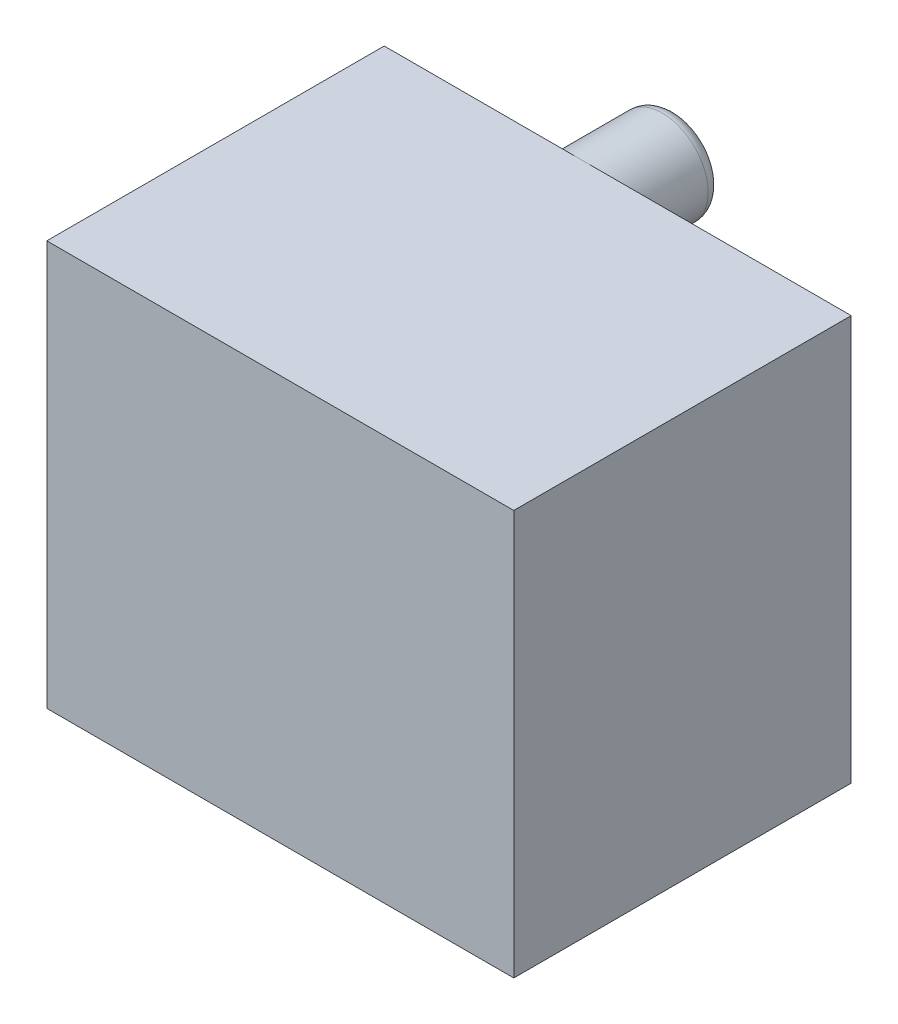
SolidWorks part; units mm, degrees
ref_plane "Front Plane" through (0, 0, 0) normal (0, 0, 1) x (1, 0, 0)
ref_plane "Top Plane" through (0, 0, 0) normal (0, 1, 0) x (1, 0, 0)
ref_plane "Right Plane" through (0, 0, 0) normal (1, 0, 0) x (0, 0, -1)
sketch "Sketch1" plane through (0, 0, 0) normal (0, 0, 1) x (1, 0, 0)
  line L1 (-8.65, 7.5) -> (8.65, 7.5)
  line L2 (-8.65, 7.5) -> (-8.65, -7.5)
  line L3 (-8.65, -7.5) -> (8.65, -7.5)
  line L4 (8.65, 7.5) -> (8.65, -7.5)
  line L5 (-8.65, 7.5) -> (8.65, -7.5) construction
  line L6 (-8.65, -7.5) -> (8.65, 7.5) construction
  point P0 (0, 0)
  dimension "D1" = 17.3
  dimension "D2" = 15
extrude "Boss-Extrude1" add sketch "Sketch1" along normal blind 12.5
sketch "Sketch2" plane through (-8.65, 0, 0) normal (-1, 0, 0) x (0, 0, 1)
  line L0 (12.5, 0) -> (0, 0) construction
  line L1 (12.5, 7.5) -> (12.5, -7.5) construction
  line L2 (0, 7.5) -> (0, -7.5) construction
  line L3 (10.5, 5) -> (10.5, -5)
  line L4 (10.5, -5) -> (8.5, -5)
  line L5 (8.5, -5) -> (8.5, -5.7)
  line L6 (8.5, -5.7) -> (5.6, -5.7)
  line L7 (5.6, -5.7) -> (5.6, -5)
  line L8 (5.6, -5) -> (3.3, -5)
  line L9 (3.3, -5) -> (3.3, -3.5)
  line L10 (3.3, -3.5) -> (2, -3.5)
  line L11 (2, -3.5) -> (2, -2)
  line L12 (2, -2) -> (1, -2)
  line L13 (1, -2) -> (1, 2)
  line L14 (12.5, -7.5) -> (0, -7.5) construction
  line L15 (2, 2) -> (1, 2)
  line L16 (2, 3.5) -> (2, 2)
  line L17 (3.3, 3.5) -> (2, 3.5)
  line L18 (3.3, 5) -> (3.3, 3.5)
  line L19 (5.6, 5) -> (3.3, 5)
  line L20 (5.6, 5.7) -> (5.6, 5)
  line L21 (8.5, 5.7) -> (5.6, 5.7)
  line L22 (8.5, 5) -> (8.5, 5.7)
  line L23 (10.5, 5) -> (8.5, 5)
  point P21 (1, 0)
  point P30 (10.5, 0)
  dimension "D1" = 1
  dimension "D2" = 1.8
  dimension "D3" = 2
  dimension "D4" = 2.5
  dimension "D5" = 4
  dimension "D6" = 5.6
  dimension "D7" = 3.3
  dimension "D8" = 4
  dimension "D9" = 2
  dimension "D10" = 5.5
extrude "Cut-Extrude1" cut sketch "Sketch2" against normal offset from surface (15.3 mm away) 2 up to face at (8.65, 0, 6.25)
sketch "Sketch3" plane through (0, 0, 0) normal (0, 0, -1) x (-1, 0, 0)
  line L0 (8.65, 7.5) -> (8.65, -7.5) construction
  line L2 (-8.65, 7.5) -> (8.65, 7.5) construction
  line L3 (0, 0) -> (8.65, 0) construction
  line L4 (3.05, 3.4986) -> (3.05, 7.5) construction
  circle A0 centre (1.35, 5.8) radius 1.7
  circle A1 centre (1.35, -5.8) radius 1.7
  dimension "D1" = 3.4
  dimension "D2" = 7.3
  dimension "D3" = 5.6
extrude "Boss-Extrude2" add sketch "Sketch3" along normal offset from surface (3.5 mm away) 16 up to face at (0, 0, 12.5)
fillet "Fillet1" radius 0.5 2 edges at (0.35, -5.8, -3.5) (0.35, 5.8, -3.5)
